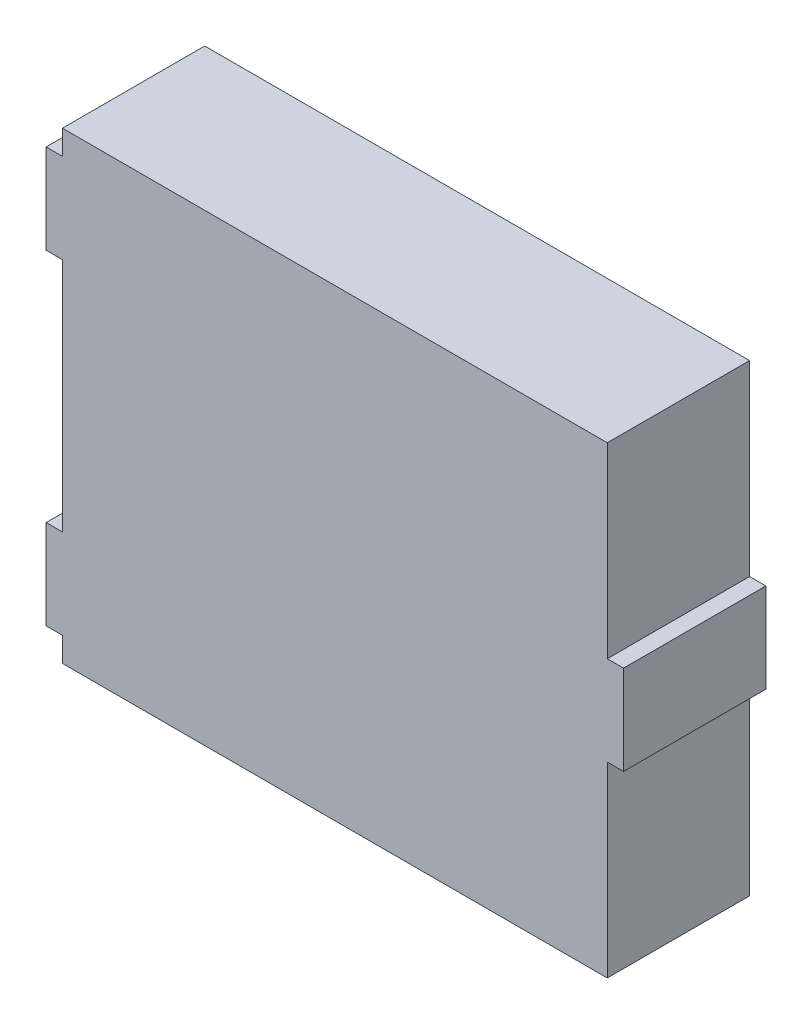
SolidWorks part; units mm, degrees
ref_plane "前视基准面" through (0, 0, 0) normal (0, 0, 1) x (1, 0, 0)
ref_plane "上视基准面" through (0, 0, 0) normal (0, 1, 0) x (1, 0, 0)
ref_plane "右视基准面" through (0, 0, 0) normal (1, 0, 0) x (0, 0, -1)
sketch "草图1" plane through (0, 0, 0) normal (0, 0, 1) x (1, 0, 0)
  line L0 (-3.35, -2.85) -> (-3.35, -2.55)
  line L1 (-3.35, -2.55) -> (-3.55, -2.55)
  line L2 (-3.55, -2.55) -> (-3.55, -1.45)
  line L3 (-3.55, -1.45) -> (-3.35, -1.45)
  line L4 (-3.35, -1.45) -> (-3.35, 1.45)
  line L5 (-3.35, 1.45) -> (-3.55, 1.45)
  line L6 (-3.55, 1.45) -> (-3.55, 2.55)
  line L7 (-3.55, 2.55) -> (-3.35, 2.55)
  line L8 (-3.35, 2.55) -> (-3.35, 2.85)
  line L9 (-3.35, 2.85) -> (3.35, 2.85)
  line L10 (3.35, 2.85) -> (3.35, 0.55)
  line L11 (3.35, 0.55) -> (3.55, 0.55)
  line L12 (3.55, 0.55) -> (3.55, -0.55)
  line L13 (3.55, -0.55) -> (3.35, -0.55)
  line L14 (3.35, -0.55) -> (3.35, -2.85)
  line L15 (3.35, -2.85) -> (-3.35, -2.85)
extrude "Component_Outline" add sketch "草图1" along normal blind 1.75 separate body
sketch3d "3D草图1"
  line L0 (0, 0, 0) -> (1, 0, 0)
  line L1 (0, 0, 0) -> (0, 1, 0)
  line L2 (0, 0, 0) -> (0, 0, 1)
  point P0 (0, 0, 0)
